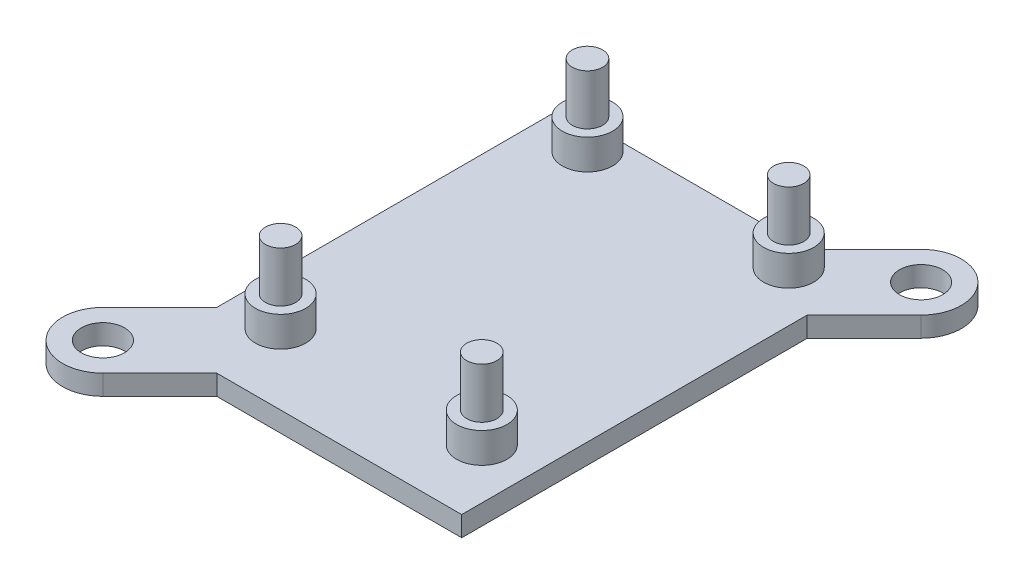
SolidWorks part; units mm, degrees
ref_plane "Front Plane" through (0, 0, 0) normal (0, 0, 1) x (1, 0, 0)
ref_plane "Top Plane" through (0, 0, 0) normal (0, 1, 0) x (1, 0, 0)
ref_plane "Right Plane" through (0, 0, 0) normal (1, 0, 0) x (0, 0, -1)
sketch "Sketch1" plane through (0, 0, 0) normal (0, 1, 0) x (1, 0, 0)
  line L0 (0, 0) -> (30, 0)
  line L1 (30, 0) -> (30, -40)
  line L2 (30, -40) -> (0, -40)
  line L3 (0, -40) -> (0, 0)
  line L4 (30, 0) -> (35.6569, 5.6569) construction
  line L5 (32.8284, 2.8284) -> (35.6569, 0) construction
  line L6 (32.8284, 2.8284) -> (30, 5.6569) construction
  line L7 (35.6569, 0) -> (30, -5.6569)
  line L8 (30, -5.6569) -> (30, 0)
  line L9 (30, 5.6569) -> (24.3431, 0)
  line L10 (24.3431, 0) -> (30, -5.6569)
  line L11 (0, -40) -> (-5.6569, -45.6569) construction
  line L12 (-2.8284, -42.8284) -> (0, -45.6569) construction
  line L13 (-2.8284, -42.8284) -> (-5.6569, -40) construction
  line L14 (-5.6569, -40) -> (0, -34.3431)
  line L15 (0, -45.6569) -> (5.6569, -40)
  line L16 (5.6569, -40) -> (0, -34.3431)
  circle A0 centre (32.8284, 2.8284) radius 2.15
  arc A1 (30, 5.6569) -> (35.6569, 0) centre (32.8284, 2.8284) cw
  circle A2 centre (-2.8284, -42.8284) radius 2.15
  arc A3 (-5.6569, -40) -> (0, -45.6569) centre (-2.8284, -42.8284) ccw
  dimension "D4" = 4.3
  dimension "D8" = 4.3
  dimension "D1" = 30
  dimension "D2" = 40
  dimension "D3" = 8
  dimension "D5" = 4
  dimension "D6" = 4
  dimension "D7" = 8
  dimension "D9" = 4
extrude "Boss-Extrude1" add sketch "Sketch1" along normal blind 2 contours L10 L0 L3 L2 L1 | A1 L9 L0 L1 L7 A0 | L0 L10 L1 | L14 A3 L15 L2 L3 A2 | L2 L16 L3
sketch "Sketch2" plane through (0, 0, 0) normal (0, 1, 0) x (1, 0, 0)
  line L0 (15, 0) -> (15, -40) construction
  line L3 (15, -2.5) -> (25, -2.5) construction
  line L4 (25, -2.5) -> (25, -33) construction
  line L5 (15, -2.5) -> (5, -2.5) construction
  line L6 (5, -2.5) -> (5, -33) construction
  line L7 (0, 0) -> (24.3431, 0) construction
  circle A0 centre (25, -2.5) radius 1.5
  circle A1 centre (25, -33) radius 1.5
  circle A2 centre (5, -33) radius 1.5
  circle A3 centre (5, -2.5) radius 1.5
  point P2 (0, 0)
  dimension "D2" = 3
  dimension "D5" = 3
  dimension "D6" = 3
  dimension "D7" = 3
  dimension "D1" = 10
  dimension "D3" = 2.5
  dimension "D4" = 30.5
  dimension "D8" = 30.5
  dimension "D9" = 2.5
  dimension "D10" = 10
extrude "Boss-Extrude2" add sketch "Sketch2" along normal blind 10 contours A3 | A2 | A1 | A0
sketch "Sketch3" plane through (0, 0, 0) normal (0, 1, 0) x (1, 0, 0)
  circle A0 centre (5, -2.5) radius 2.5
  circle A1 centre (25, -2.5) radius 2.5
  circle A2 centre (25, -33) radius 2.5
  circle A4 centre (5, -33) radius 2.5
  dimension "D1" = 5
  dimension "D2" = 5
extrude "Boss-Extrude3" add sketch "Sketch3" along normal blind 5
